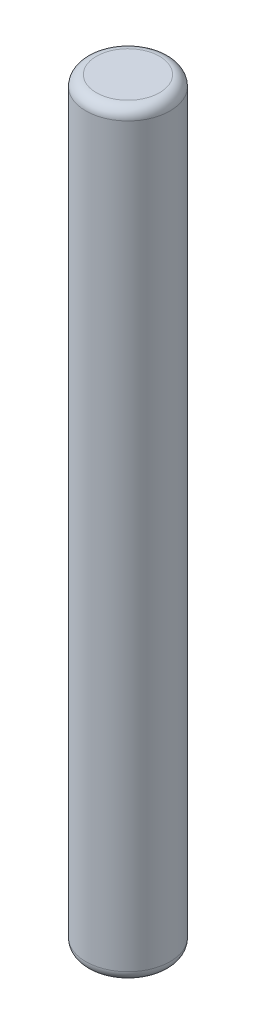
SolidWorks part; units mm, degrees
ref_plane "Face" through (0, 0, 0) normal (0, 0, 1) x (1, 0, 0)
ref_plane "Dessus" through (0, 0, 0) normal (0, 1, 0) x (1, 0, 0)
ref_plane "Droite" through (0, 0, 0) normal (1, 0, 0) x (0, 0, -1)
sketch "Esquisse1" plane through (0, 0, 0) normal (0, 1, 0) x (1, 0, 0)
  circle A0 centre (0, 0) radius 1
  dimension "D1" = 2
extrude "Boss.-Extru.1" add sketch "Esquisse1" along normal blind 18
fillet "Congé1" radius 0.25 2 edges at (0, 0, 1) (0, 18, 1)
